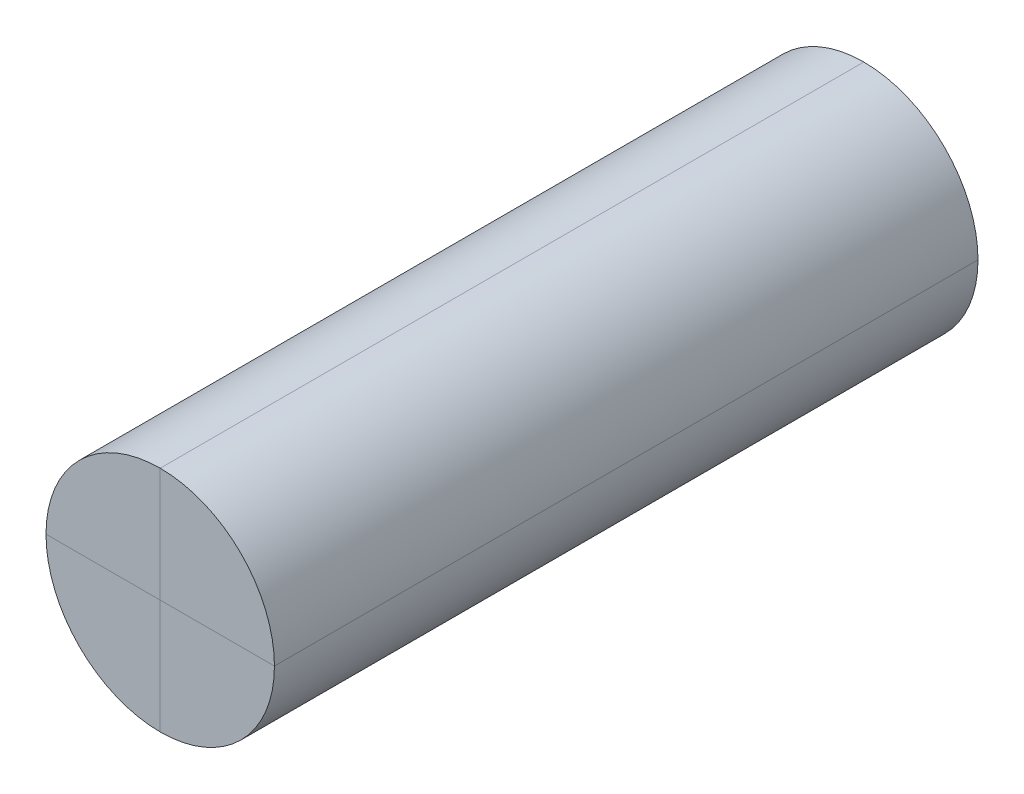
SolidWorks part; units mm, degrees
ref_plane "Front Plane" through (0, 0, 0) normal (0, 0, 1) x (1, 0, 0)
ref_plane "Top Plane" through (0, 0, 0) normal (0, 1, 0) x (1, 0, 0)
ref_plane "Right Plane" through (0, 0, 0) normal (1, 0, 0) x (0, 0, -1)
other "Configuration Table"
sketch "Sketch1" plane through (0, 0, 0) normal (0, 0, 1) x (1, 0, 0)
  circle A0 centre (0, 0) radius 3.81
  dimension "D1" = 7.62
extrude "Extrude1" add sketch "Sketch1" along normal blind 23.47
sketch "Sketch2" plane through (0, 0, 0) normal (0, 0, 1) x (1, 0, 0)
  line L0 (0, 4.9374) -> (0, -4.6909)
split line "Split Line3"
sketch "Sketch3" plane through (0, 0, 0) normal (0, 0, 1) x (1, 0, 0)
  line L0 (-4.958, 0) -> (4.6978, 0)
split line "Split Line4"
